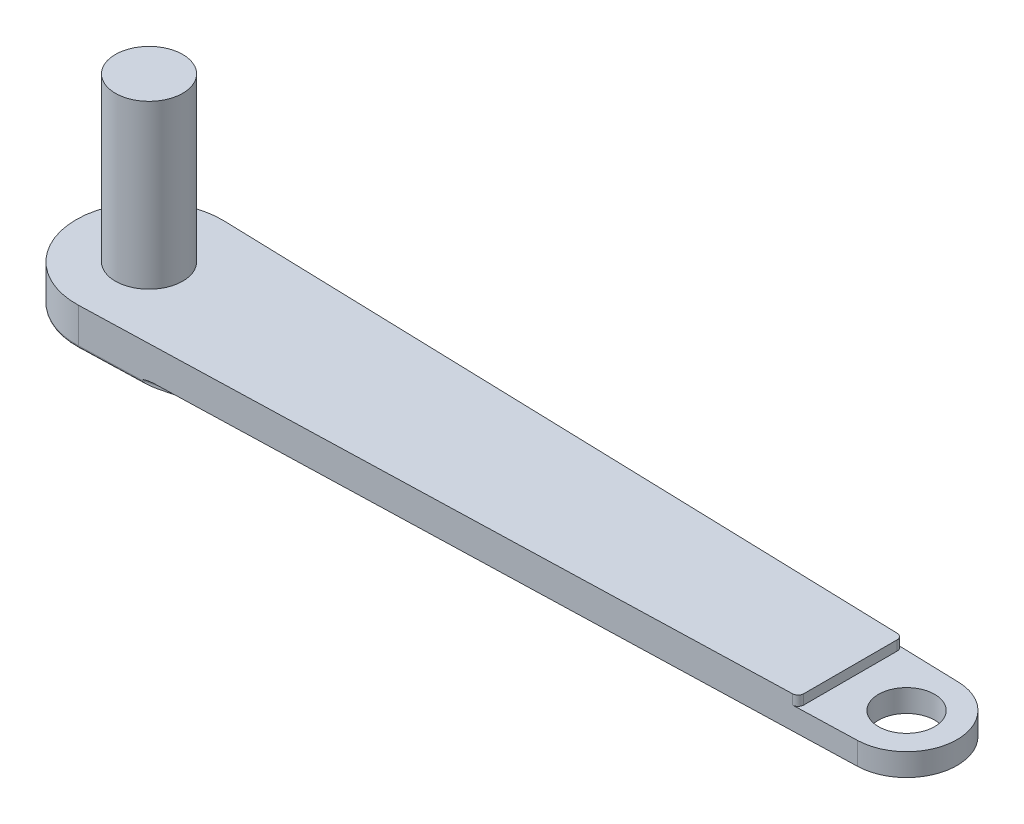
SolidWorks part; units mm, degrees
ref_plane "Front Plane" through (0, 0, 0) normal (0, 0, 1) x (1, 0, 0)
ref_plane "Top Plane" through (0, 0, 0) normal (0, 1, 0) x (1, 0, 0)
ref_plane "Right Plane" through (0, 0, 0) normal (1, 0, 0) x (0, 0, -1)
sketch "Sketch2" plane through (0, 0, 0) normal (0, 1, 0) x (1, 0, 0)
  line L0 (-36.9106, 0) -> (120.0894, 0) construction
  line L1 (-23.5254, 12.9943) -> (111.3561, 8.996)
  line L2 (-23.5254, -12.9943) -> (111.3561, -8.996)
  circle A0 centre (111.0894, 0) radius 5
  arc A1 (111.3561, -8.996) -> (111.3561, 8.996) centre (111.0894, 0) ccw
  arc A2 (-23.5254, 12.9943) -> (-23.5254, -12.9943) centre (-23.9106, 0) ccw
  dimension "D1" = 18
  dimension "D2" = 10
  dimension "D3" = 26
  dimension "D4" = 135
extrude "Boss-Extrude1" add sketch "Sketch2" along normal blind 6.75
sketch "Sketch6" plane through (0, 6.75, 0) normal (0, 1, 0) x (1, 0, 0)
  line L0 (101.0894, 0) -> (101.0894, 15.9577)
  line L1 (101.0894, 15.9577) -> (123.6962, 15.9577)
  line L2 (123.6962, 15.9577) -> (123.6962, -15.6622)
  line L3 (123.6962, -15.6622) -> (101.0894, -15.6622)
  line L4 (101.0894, -15.6622) -> (101.0894, 0)
  circle A0 centre (111.0894, 0) radius 5 construction
  dimension "D1" = 10
extrude "Cut-Extrude2" cut sketch "Sketch6" against normal blind 1.75
fillet "Fillet1" radius 1 2 edges at (101.0894, 5.875, -9.3004) (101.0894, 5.875, 9.3004)
sketch "Sketch9" plane through (0, 0, 0) normal (0, -1, 0) x (1, 0, 0)
  line L0 (-23.5254, 12.9943) -> (111.3561, 8.996) construction
  line L1 (-12.4521, 12.6661) -> (77.5479, 9.9982)
  line L2 (77.5479, -9.9982) -> (-12.4521, 12.6661)
  line L3 (111.3561, -8.996) -> (-23.5254, -12.9943) construction
  arc A0 (77.5479, -9.9982) -> (77.5479, 9.9982) centre (111.0894, 0) ccw
  dimension "D1" = 70
  dimension "D2" = 90
extrude "Cut-Extrude4" cut sketch "Sketch9" against normal blind 1
fillet "Fillet2" radius 0.5 1 edges at (32.5479, 1, 1.3339)
fillet "Fillet3" radius 0.5 3 edges at (-17.9888, 0, 12.8302) (-36.9106, 0, 0) (27.0112, 0, -11.4963)
sketch "Sketch10" plane through (0, 6.75, 0) normal (0, 1, 0) x (1, 0, 0)
  circle A0 centre (-23.9106, 0) radius 6
  dimension "D1" = 12
extrude "Boss-Extrude2" add sketch "Sketch10" along normal blind 29
sketch "Sketch11" plane through (0, 0, 0) normal (0, -1, 0) x (1, 0, 0)
  circle A0 centre (-23.9106, 0) radius 2.5
  dimension "D1" = 5
extrude "Cut-Extrude6" cut sketch "Sketch11" against normal blind 20
